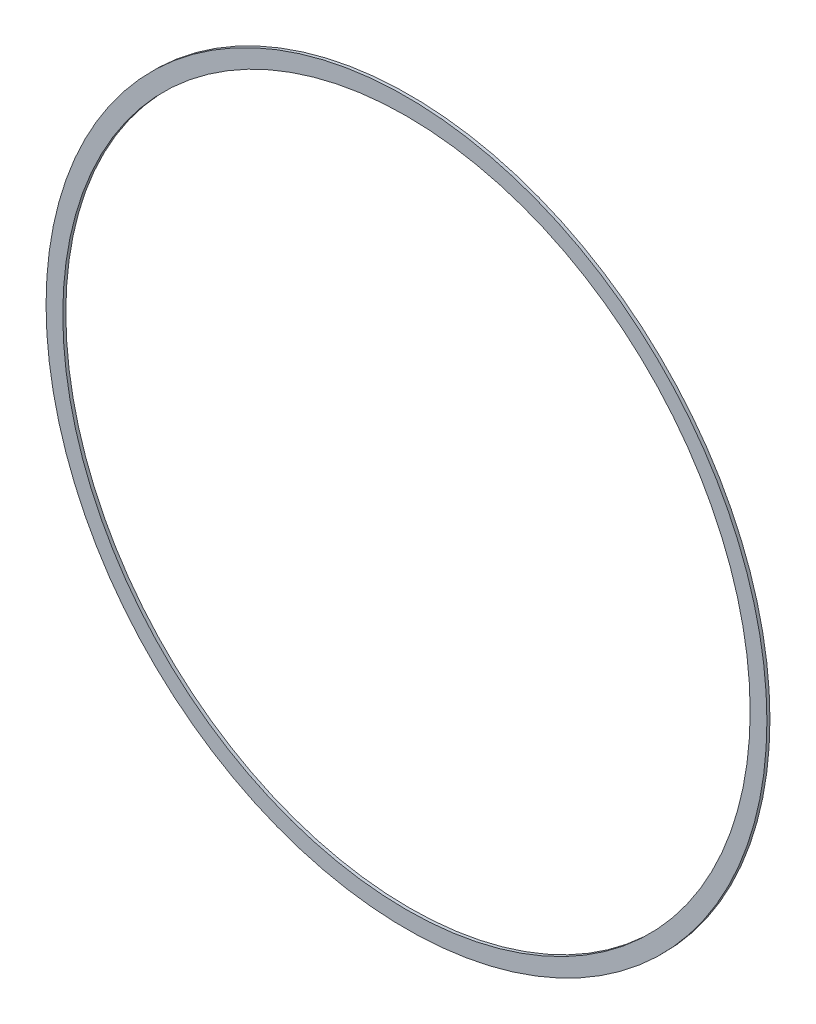
SolidWorks part; units mm, degrees
material "ASTM A36 Steel"
ref_plane "Front Plane" through (0, 0, 0) normal (0, 0, 1) x (1, 0, 0)
ref_plane "Top Plane" through (0, 0, 0) normal (0, 1, 0) x (1, 0, 0)
ref_plane "Right Plane" through (0, 0, 0) normal (1, 0, 0) x (0, 0, -1)
sketch "Sketch1" plane through (0, 0, 0) normal (0, 0, 1) x (1, 0, 0)
  circle A0 centre (0, 0) radius 237
  dimension "D1" = 474
extrude "Extrude-Thin1" add sketch "Sketch1" along normal blind 2 thin thin type one direction reverse wall 11
